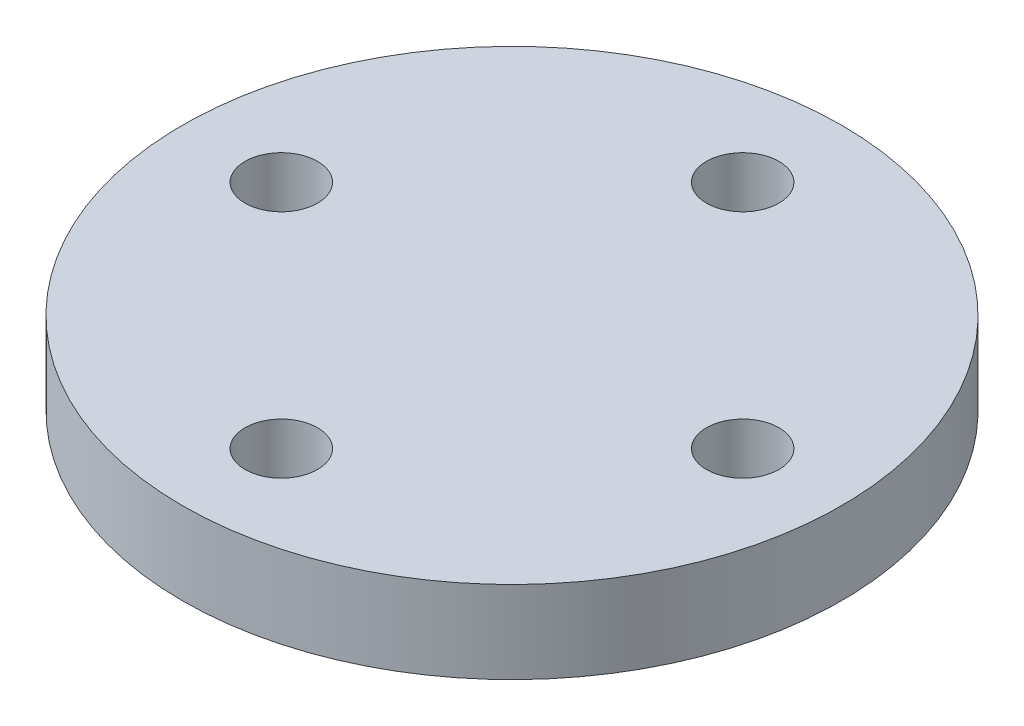
SolidWorks part; units mm, degrees
ref_plane "Front Plane" through (0, 0, 0) normal (0, 0, 1) x (1, 0, 0)
ref_plane "Top Plane" through (0, 0, 0) normal (0, 1, 0) x (1, 0, 0)
ref_plane "Right Plane" through (0, 0, 0) normal (1, 0, 0) x (0, 0, -1)
sketch "Sketch1" plane through (0, 0, 0) normal (0, 1, 0) x (1, 0, 0)
  circle A0 centre (0, 0) radius 10
  circle A1 centre (0, 0) radius 7 construction
  circle A2 centre (0, 7) radius 1.1
  circle A3 centre (7, 0) radius 1.1
  circle A4 centre (0, -7) radius 1.1
  circle A5 centre (-7, 0) radius 1.1
  dimension "D1" = 20
  dimension "D2" = 14
  dimension "D3" = 2.2
extrude "Boss-Extrude1" add sketch "Sketch1" along normal blind 2.5
